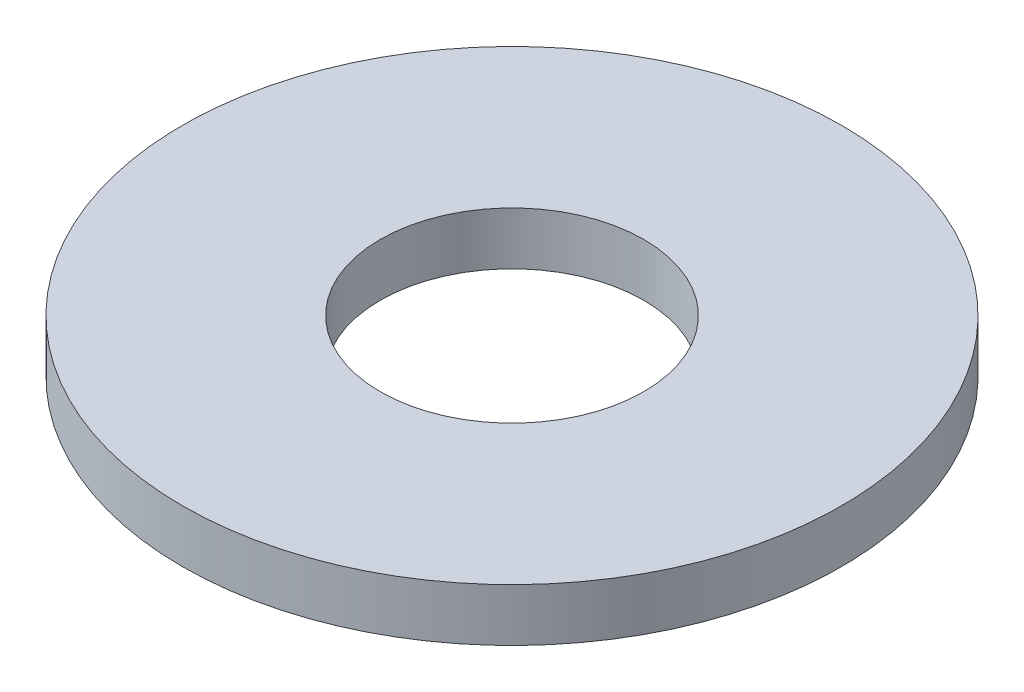
SolidWorks part; units mm, degrees
ref_plane "Front Plane" through (0, 0, 0) normal (0, 0, 1) x (1, 0, 0)
ref_plane "Top Plane" through (0, 0, 0) normal (0, 1, 0) x (1, 0, 0)
ref_plane "Right Plane" through (0, 0, 0) normal (1, 0, 0) x (0, 0, -1)
sketch "Sketch1" plane through (0, 0, 0) normal (0, 1, 0) x (1, 0, 0)
  circle A0 centre (0, 0) radius 2
  circle A1 centre (0, 0) radius 5
  dimension "D1" = 4
  dimension "D2" = 10
extrude "Boss-Extrude1" add sketch "Sketch1" along normal mid plane 0.8
